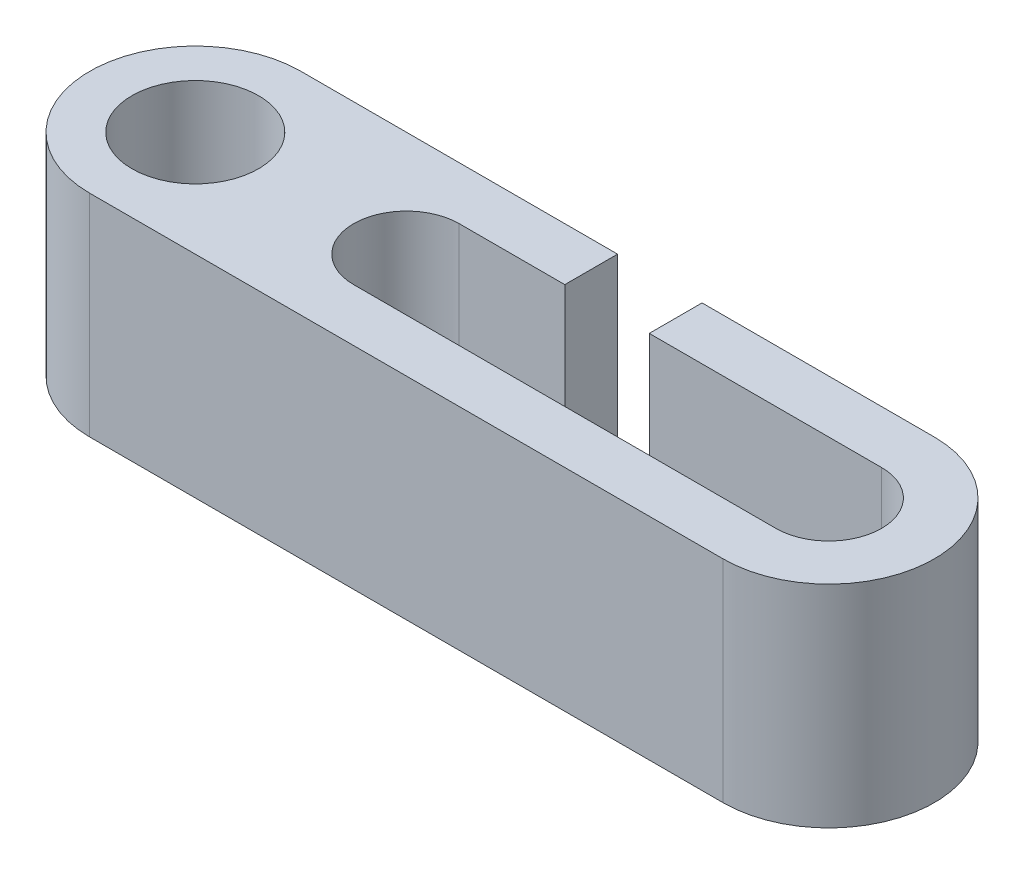
SolidWorks part; units mm, degrees
ref_plane "Front Plane" through (0, 0, 0) normal (0, 0, 1) x (1, 0, 0)
ref_plane "Top Plane" through (0, 0, 0) normal (0, 1, 0) x (1, 0, 0)
ref_plane "Right Plane" through (0, 0, 0) normal (1, 0, 0) x (0, 0, -1)
sketch "Sketch1" plane through (0, 0, 0) normal (0, 1, 0) x (1, 0, 0)
  line L0 (-45.8925, 10.0214) -> (-15.8925, 10.0214) construction
  line L1 (-45.8925, 15.0214) -> (-30.8925, 15.0214)
  line L2 (-45.8925, 5.0214) -> (-15.8925, 5.0214)
  line L3 (-35.8925, 10.0214) -> (-15.8925, 10.0214) construction
  line L4 (-35.8925, 12.5214) -> (-30.8925, 12.5214)
  line L5 (-35.8925, 7.5214) -> (-15.8925, 7.5214)
  line L6 (-26.8925, 15.0214) -> (-15.8925, 15.0214)
  line L8 (-30.8925, 12.5214) -> (-30.8925, 15.0214)
  line L10 (-26.8925, 12.5214) -> (-26.8925, 15.0214)
  line L11 (-26.8925, 12.5214) -> (-15.8925, 12.5214)
  arc A0 (-45.8925, 15.0214) -> (-45.8925, 5.0214) centre (-45.8925, 10.0214) ccw
  arc A1 (-15.8925, 5.0214) -> (-15.8925, 15.0214) centre (-15.8925, 10.0214) ccw
  circle A2 centre (-45.8925, 10.0214) radius 3
  arc A3 (-35.8925, 12.5214) -> (-35.8925, 7.5214) centre (-35.8925, 10.0214) ccw
  arc A4 (-15.8925, 7.5214) -> (-15.8925, 12.5214) centre (-15.8925, 10.0214) ccw
  point P2 (-30.8925, 10.5214)
  point P11 (-25.8925, 10.5214)
  dimension "D1" = 5
  dimension "D3" = 6
  dimension "D4" = 2.5
  dimension "D2" = 30
  dimension "D5" = 10
  dimension "D6" = 4
extrude "Boss-Extrude1" add sketch "Sketch1" along normal blind 10
